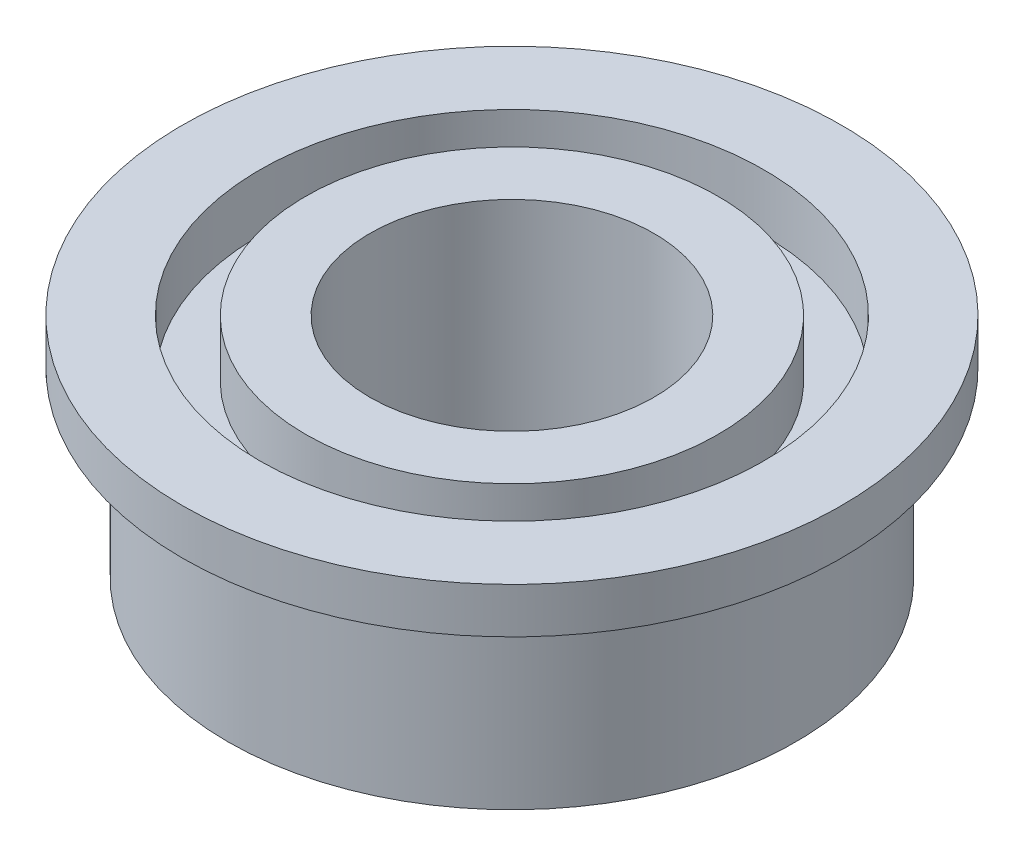
SolidWorks part; units mm, degrees
ref_plane "Front Plane" through (0, 0, 0) normal (0, 0, 1) x (1, 0, 0)
ref_plane "Top Plane" through (0, 0, 0) normal (0, 1, 0) x (1, 0, 0)
ref_plane "Right Plane" through (0, 0, 0) normal (1, 0, 0) x (0, 0, -1)
sketch "Sketch1" plane through (0, 0, 0) normal (0, 1, 0) x (1, 0, 0)
  circle A0 centre (0, 0) radius 5
  circle A1 centre (0, 0) radius 2.5
  dimension "D1" = 10
  dimension "D2" = 5
extrude "Boss-Extrude1" add sketch "Sketch1" along normal blind 3.2
sketch "Sketch2" plane through (0, 3.2, 0) normal (0, 1, 0) x (1, 0, 0)
  circle A0 centre (0, 0) radius 5.8
  circle A1 centre (0, 0) radius 2.5
  dimension "D1" = 11.6
extrude "Boss-Extrude2" add sketch "Sketch2" along normal blind 0.8
sketch "Sketch3" plane through (0, 0, 0) normal (0, -1, 0) x (1, 0, 0)
  circle A0 centre (0, 0) radius 4.3551
  circle A1 centre (0, 0) radius 3.6921
extrude "Cut-Extrude1" cut sketch "Sketch3" against normal blind 1
sketch "Sketch4" plane through (0, 4, 0) normal (0, 1, 0) x (1, 0, 0)
  circle A0 centre (0, 0) radius 4.4373
  circle A1 centre (0, 0) radius 3.6299
extrude "Cut-Extrude2" cut sketch "Sketch4" against normal blind 1
